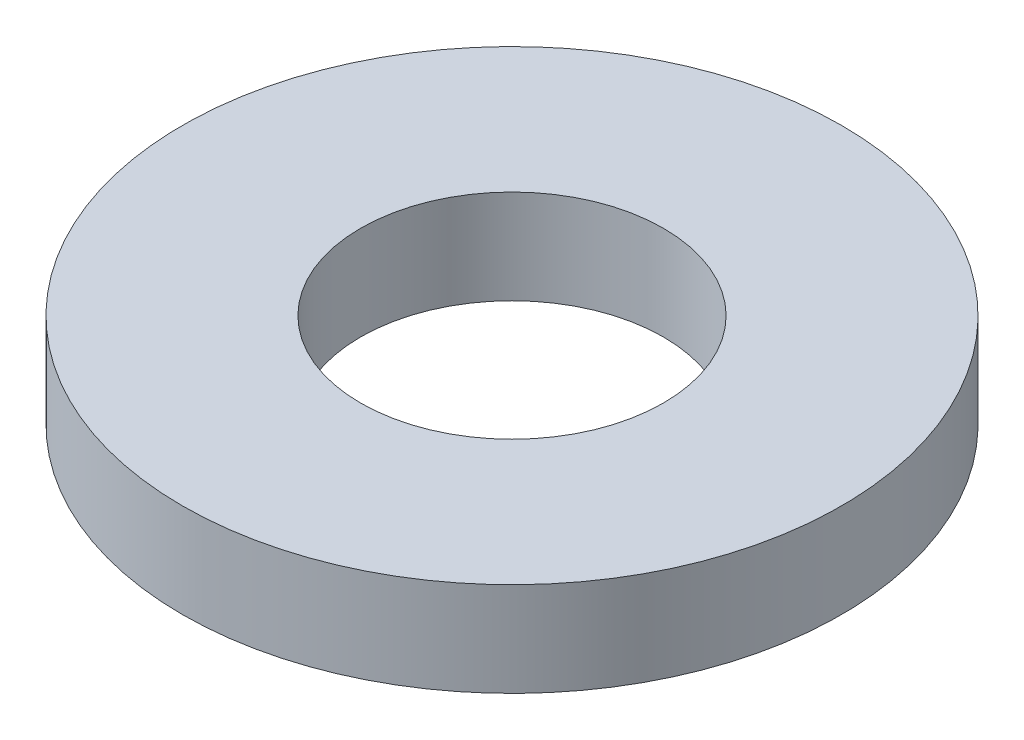
SolidWorks part; units mm, degrees
material "6061-T6 (SS)"
ref_plane "Front Plane" through (0, 0, 0) normal (0, 0, 1) x (1, 0, 0)
ref_plane "Top Plane" through (0, 0, 0) normal (0, 1, 0) x (1, 0, 0)
ref_plane "Right Plane" through (0, 0, 0) normal (1, 0, 0) x (0, 0, -1)
sketch "Sketch1" plane through (0, 0, 0) normal (0, 1, 0) x (1, 0, 0)
  circle A0 centre (0, 0) radius 2.5527
  circle A1 centre (0, 0) radius 5.5562
  dimension "D1" = 5.1054
  dimension "D2" = 11.1125
extrude "Boss-Extrude1" add sketch "Sketch1" along normal blind 1.5875
